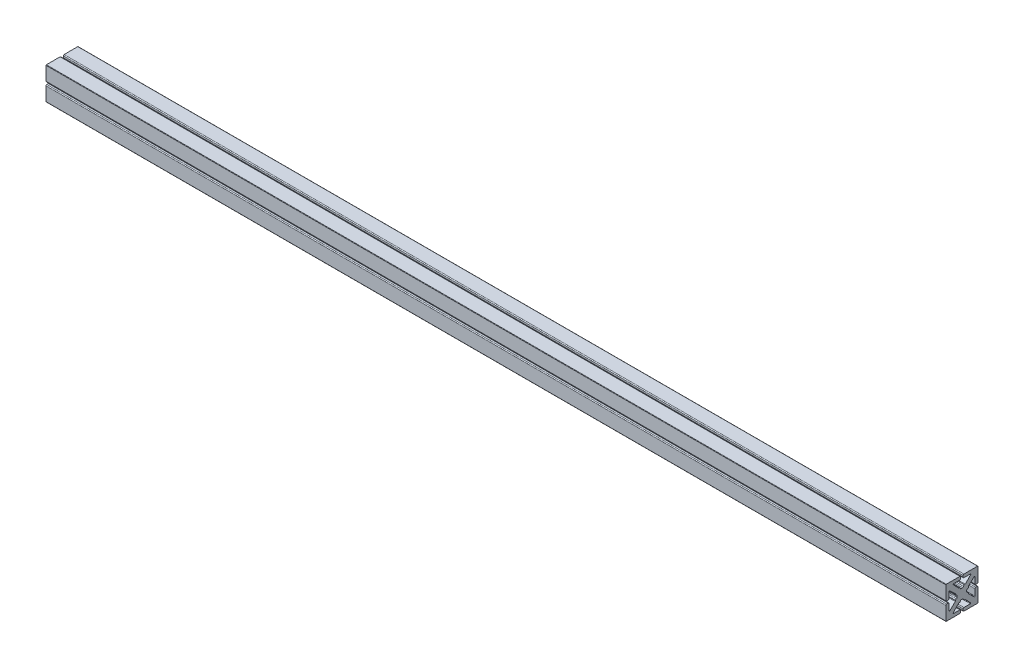
SolidWorks part; units mm, degrees
material "1060 Alloy"
ref_plane "Front Plane" through (0, 0, 0) normal (0, 0, 1) x (1, 0, 0)
ref_plane "Top Plane" through (0, 0, 0) normal (0, 1, 0) x (1, 0, 0)
ref_plane "Right Plane" through (0, 0, 0) normal (1, 0, 0) x (0, 0, -1)
sketch "Sketch1" plane through (0, 0, 0) normal (1, 0, 0) x (0, 0, -1)
  line L0 (0, 0) -> (0, 1.4986) construction
  line L1 (-0.2413, 1.4986) -> (0.2413, 1.4986)
  line L2 (5.0038, 0.635) -> (5.0038, 4.8768)
  line L3 (0.7493, 2.0066) -> (0.8825, 2.0066)
  line L4 (1.0655, 2.0845) -> (2.7141, 3.7982)
  line L5 (2.6226, 4.0132) -> (0.635, 4.0132)
  line L6 (0.381, 4.2672) -> (0.381, 4.7498)
  line L7 (0.635, 5.0038) -> (4.8768, 5.0038)
  line L8 (5.0038, 5.0038) -> (0, 0) construction
  line L9 (0, 0) -> (8.6271, 0) construction
  line L10 (0, 0) -> (0, 5.0038) construction
  line L11 (4.2672, 0.381) -> (4.7498, 0.381)
  line L12 (4.0132, 2.6226) -> (4.0132, 0.635)
  line L13 (2.0845, 1.0655) -> (3.7982, 2.7141)
  line L14 (2.0066, 0.7493) -> (2.0066, 0.8825)
  line L15 (1.4986, -0.2413) -> (1.4986, 0.2413)
  line L16 (0, 0) -> (1.4986, 0) construction
  line L17 (-0.2413, -1.4986) -> (0.2413, -1.4986)
  line L18 (0.7493, -2.0066) -> (0.8825, -2.0066)
  line L19 (1.0655, -2.0845) -> (2.7141, -3.7982)
  line L20 (2.6226, -4.0132) -> (0.635, -4.0132)
  line L21 (0.381, -4.2672) -> (0.381, -4.7498)
  line L22 (0.635, -5.0038) -> (4.8768, -5.0038)
  line L23 (5.0038, -0.635) -> (5.0038, -4.8768)
  line L24 (4.2672, -0.381) -> (4.7498, -0.381)
  line L25 (4.0132, -2.6226) -> (4.0132, -0.635)
  line L26 (2.0845, -1.0655) -> (3.7982, -2.7141)
  line L27 (2.0066, -0.7493) -> (2.0066, -0.8825)
  line L28 (-0.7493, 2.0066) -> (-0.8825, 2.0066)
  line L29 (-1.0655, 2.0845) -> (-2.7141, 3.7982)
  line L30 (-2.6226, 4.0132) -> (-0.635, 4.0132)
  line L31 (-0.381, 4.2672) -> (-0.381, 4.7498)
  line L32 (-0.635, 5.0038) -> (-4.8768, 5.0038)
  line L33 (-5.0038, 0.635) -> (-5.0038, 4.8768)
  line L34 (-4.2672, 0.381) -> (-4.7498, 0.381)
  line L35 (-4.0132, 2.6226) -> (-4.0132, 0.635)
  line L36 (-2.0845, 1.0655) -> (-3.7982, 2.7141)
  line L37 (-2.0066, 0.7493) -> (-2.0066, 0.8825)
  line L38 (-1.4986, -0.2413) -> (-1.4986, 0.2413)
  line L39 (-2.0066, -0.7493) -> (-2.0066, -0.8825)
  line L40 (-2.0845, -1.0655) -> (-3.7982, -2.7141)
  line L41 (-4.0132, -2.6226) -> (-4.0132, -0.635)
  line L42 (-4.2672, -0.381) -> (-4.7498, -0.381)
  line L43 (-5.0038, -0.635) -> (-5.0038, -4.8768)
  line L44 (-0.635, -5.0038) -> (-4.8768, -5.0038)
  line L45 (-0.381, -4.2672) -> (-0.381, -4.7498)
  line L46 (-2.6226, -4.0132) -> (-0.635, -4.0132)
  line L47 (-1.0655, -2.0845) -> (-2.7141, -3.7982)
  line L48 (-0.7493, -2.0066) -> (-0.8825, -2.0066)
  arc A0 (2.7141, 3.7982) -> (2.6226, 4.0132) centre (2.6226, 3.8862) ccw
  arc A1 (0.4953, 1.7526) -> (0.7493, 2.0066) centre (0.7493, 1.7526) cw
  arc A2 (0.8825, 2.0066) -> (1.0655, 2.0845) centre (0.8825, 2.2606) ccw
  arc A3 (0.635, 4.0132) -> (0.381, 4.2672) centre (0.635, 4.2672) cw
  arc A4 (0.381, 4.7498) -> (0.635, 5.0038) centre (0.635, 4.7498) cw
  arc A5 (0.2413, 1.4986) -> (0.4953, 1.7526) centre (0.2413, 1.7526) ccw
  arc A6 (4.7498, 0.381) -> (5.0038, 0.635) centre (4.7498, 0.635) ccw
  arc A7 (4.0132, 0.635) -> (4.2672, 0.381) centre (4.2672, 0.635) ccw
  arc A8 (3.7982, 2.7141) -> (4.0132, 2.6226) centre (3.8862, 2.6226) cw
  arc A9 (2.0066, 0.8825) -> (2.0845, 1.0655) centre (2.2606, 0.8825) cw
  arc A10 (1.7526, 0.4953) -> (2.0066, 0.7493) centre (1.7526, 0.7493) ccw
  arc A11 (1.4986, 0.2413) -> (1.7526, 0.4953) centre (1.7526, 0.2413) cw
  arc A12 (0.2413, -1.4986) -> (0.4953, -1.7526) centre (0.2413, -1.7526) cw
  arc A13 (0.4953, -1.7526) -> (0.7493, -2.0066) centre (0.7493, -1.7526) ccw
  arc A14 (0.8825, -2.0066) -> (1.0655, -2.0845) centre (0.8825, -2.2606) cw
  arc A15 (2.7141, -3.7982) -> (2.6226, -4.0132) centre (2.6226, -3.8862) cw
  arc A16 (0.635, -4.0132) -> (0.381, -4.2672) centre (0.635, -4.2672) ccw
  arc A17 (0.381, -4.7498) -> (0.635, -5.0038) centre (0.635, -4.7498) ccw
  arc A18 (4.7498, -0.381) -> (5.0038, -0.635) centre (4.7498, -0.635) cw
  arc A19 (4.0132, -0.635) -> (4.2672, -0.381) centre (4.2672, -0.635) cw
  arc A20 (3.7982, -2.7141) -> (4.0132, -2.6226) centre (3.8862, -2.6226) ccw
  arc A21 (2.0066, -0.8825) -> (2.0845, -1.0655) centre (2.2606, -0.8825) ccw
  arc A22 (1.7526, -0.4953) -> (2.0066, -0.7493) centre (1.7526, -0.7493) cw
  arc A23 (1.4986, -0.2413) -> (1.7526, -0.4953) centre (1.7526, -0.2413) ccw
  arc A24 (-0.2413, 1.4986) -> (-0.4953, 1.7526) centre (-0.2413, 1.7526) cw
  arc A25 (-0.4953, 1.7526) -> (-0.7493, 2.0066) centre (-0.7493, 1.7526) ccw
  arc A26 (-0.8825, 2.0066) -> (-1.0655, 2.0845) centre (-0.8825, 2.2606) cw
  arc A27 (-2.7141, 3.7982) -> (-2.6226, 4.0132) centre (-2.6226, 3.8862) cw
  arc A28 (-0.635, 4.0132) -> (-0.381, 4.2672) centre (-0.635, 4.2672) ccw
  arc A29 (-0.381, 4.7498) -> (-0.635, 5.0038) centre (-0.635, 4.7498) ccw
  arc A30 (-4.7498, 0.381) -> (-5.0038, 0.635) centre (-4.7498, 0.635) cw
  arc A31 (-4.0132, 0.635) -> (-4.2672, 0.381) centre (-4.2672, 0.635) cw
  arc A32 (-3.7982, 2.7141) -> (-4.0132, 2.6226) centre (-3.8862, 2.6226) ccw
  arc A33 (-2.0066, 0.8825) -> (-2.0845, 1.0655) centre (-2.2606, 0.8825) ccw
  arc A34 (-1.7526, 0.4953) -> (-2.0066, 0.7493) centre (-1.7526, 0.7493) cw
  arc A35 (-1.4986, 0.2413) -> (-1.7526, 0.4953) centre (-1.7526, 0.2413) ccw
  arc A36 (-1.4986, -0.2413) -> (-1.7526, -0.4953) centre (-1.7526, -0.2413) cw
  arc A37 (-1.7526, -0.4953) -> (-2.0066, -0.7493) centre (-1.7526, -0.7493) ccw
  arc A38 (-2.0066, -0.8825) -> (-2.0845, -1.0655) centre (-2.2606, -0.8825) cw
  arc A39 (-3.7982, -2.7141) -> (-4.0132, -2.6226) centre (-3.8862, -2.6226) cw
  arc A40 (-4.0132, -0.635) -> (-4.2672, -0.381) centre (-4.2672, -0.635) ccw
  arc A41 (-4.7498, -0.381) -> (-5.0038, -0.635) centre (-4.7498, -0.635) ccw
  arc A42 (-0.381, -4.7498) -> (-0.635, -5.0038) centre (-0.635, -4.7498) cw
  arc A43 (-0.635, -4.0132) -> (-0.381, -4.2672) centre (-0.635, -4.2672) cw
  arc A44 (-2.7141, -3.7982) -> (-2.6226, -4.0132) centre (-2.6226, -3.8862) ccw
  arc A45 (-0.8825, -2.0066) -> (-1.0655, -2.0845) centre (-0.8825, -2.2606) ccw
  arc A46 (-0.4953, -1.7526) -> (-0.7493, -2.0066) centre (-0.7493, -1.7526) cw
  arc A47 (-0.2413, -1.4986) -> (-0.4953, -1.7526) centre (-0.2413, -1.7526) ccw
  arc A48 (-4.8768, 5.0038) -> (-5.0038, 4.8768) centre (-4.8768, 4.8768) ccw
  arc A49 (-5.0038, -4.8768) -> (-4.8768, -5.0038) centre (-4.8768, -4.8768) ccw
  arc A50 (4.8768, -5.0038) -> (5.0038, -4.8768) centre (4.8768, -4.8768) ccw
  arc A51 (4.8768, 5.0038) -> (5.0038, 4.8768) centre (4.8768, 4.8768) cw
  point P14 (2.921, 4.0132)
  point P19 (0.9906, 2.0066)
  point P150 (0, -1.4986)
  point P152 (-5.0038, 5.0038)
  point P155 (-5.0038, -5.0038)
  point P158 (5.0038, -5.0038)
  dimension "D10" = 0.127
  dimension "D11" = 0.254
  dimension "D2" = 0.127
  dimension "D1" = 10.0076
  dimension "D3" = 2.9972
  dimension "D4" = 0.508
  dimension "D5" = 0.762
  dimension "D6" = 0.9906
  dimension "D7" = 2.54
  dimension "D8" = 1.9812
  dimension "D9" = 0.9906
extrude "Boss-Extrude1" add sketch "Sketch1" along normal blind 2.54 contours L33 A48 L32 A29 L31 A28 L30 A27 L29 A26 L28 A25 A24 L1 A5 A1 L3 A2 L4 A0 L5 A3 L6 A4 L7 A51 L2 A6 L11 A7 L12 A8 L13 A9 L14 A10 A11 L15 A23 A22 L27 A21 L26 A20 L25 A19 L24 A18 L23 A50 L22 A17 L21 A16 L20 A15 L19 A14 L18 A13 A12 L17 A47 A46 L48 A45 L47 A44 L46 A43 L45 A42 L44 A49 L43 A41 L42 A40 L41 A39 L40 A38 L39 A37 A36 L38 A35 A34 L37 A33 L36 A32 L35 A31 L34 A30
scale "Scale1" scale about centroid uniform scaling yes scale factor 8
sketch "Sketch2" plane through (0, 0, 0) normal (1, 0, 0) x (0, 0, -1)
  line L44 (-37.9984, 3.048) -> (-34.1376, 3.048)
  line L45 (-32.1056, 5.08) -> (-32.1056, 20.9808)
  line L46 (-30.3852, 21.7129) -> (-16.676, 8.5244)
  line L47 (-16.0528, 7.06) -> (-16.0528, 5.9944)
  line L48 (-11.9888, 1.9304) -> (-11.9888, -1.9304)
  line L49 (-16.0528, -5.9944) -> (-16.0528, -7.06)
  line L50 (-16.676, -8.5244) -> (-30.3852, -21.7129)
  line L51 (-32.1056, -20.9808) -> (-32.1056, -5.08)
  line L52 (-34.1376, -3.048) -> (-37.9984, -3.048)
  line L53 (-40.0304, -5.08) -> (-40.0304, -39.0144)
  line L54 (-39.0144, -40.0304) -> (-5.08, -40.0304)
  line L55 (-3.048, -37.9984) -> (-3.048, -34.1376)
  line L56 (-5.08, -32.1056) -> (-20.9808, -32.1056)
  line L57 (-21.7129, -30.3852) -> (-8.5244, -16.676)
  line L58 (-7.06, -16.0528) -> (-5.9944, -16.0528)
  line L59 (-1.9304, -11.9888) -> (1.9304, -11.9888)
  line L60 (5.9944, -16.0528) -> (7.06, -16.0528)
  line L61 (8.5244, -16.676) -> (21.7129, -30.3852)
  line L62 (20.9808, -32.1056) -> (5.08, -32.1056)
  line L63 (3.048, -34.1376) -> (3.048, -37.9984)
  line L64 (5.08, -40.0304) -> (39.0144, -40.0304)
  line L65 (40.0304, -39.0144) -> (40.0304, -5.08)
  line L66 (37.9984, -3.048) -> (34.1376, -3.048)
  line L67 (32.1056, -5.08) -> (32.1056, -20.9808)
  line L68 (30.3852, -21.7129) -> (16.676, -8.5244)
  line L69 (16.0528, -7.06) -> (16.0528, -5.9944)
  line L70 (11.9888, -1.9304) -> (11.9888, 1.9304)
  line L71 (16.0528, 5.9944) -> (16.0528, 7.06)
  line L72 (16.676, 8.5244) -> (30.3852, 21.7129)
  line L73 (32.1056, 20.9808) -> (32.1056, 5.08)
  line L74 (34.1376, 3.048) -> (37.9984, 3.048)
  line L75 (40.0304, 5.08) -> (40.0304, 39.0144)
  line L76 (39.0144, 40.0304) -> (5.08, 40.0304)
  line L77 (3.048, 37.9984) -> (3.048, 34.1376)
  line L78 (5.08, 32.1056) -> (20.9808, 32.1056)
  line L79 (21.7129, 30.3852) -> (8.5244, 16.676)
  line L80 (7.06, 16.0528) -> (5.9944, 16.0528)
  line L81 (1.9304, 11.9888) -> (-1.9304, 11.9888)
  line L82 (-5.9944, 16.0528) -> (-7.06, 16.0528)
  line L83 (-8.5244, 16.676) -> (-21.7129, 30.3852)
  line L84 (-20.9808, 32.1056) -> (-5.08, 32.1056)
  line L85 (-3.048, 34.1376) -> (-3.048, 37.9984)
  line L86 (-5.08, 40.0304) -> (-39.0144, 40.0304)
  line L87 (-40.0304, 39.0144) -> (-40.0304, 5.08)
  line L88 (-37.9984, 3.048) -> (-34.1376, 3.048)
  line L89 (-32.1056, 5.08) -> (-32.1056, 20.9808)
  line L90 (-30.3852, 21.7129) -> (-16.676, 8.5244)
  line L91 (-16.0528, 7.06) -> (-16.0528, 5.9944)
  line L92 (-11.9888, 1.9304) -> (-11.9888, -1.9304)
  line L93 (-16.0528, -5.9944) -> (-16.0528, -7.06)
  line L94 (-16.676, -8.5244) -> (-30.3852, -21.7129)
  line L95 (-32.1056, -20.9808) -> (-32.1056, -5.08)
  line L96 (-34.1376, -3.048) -> (-37.9984, -3.048)
  line L97 (-40.0304, -5.08) -> (-40.0304, -39.0144)
  line L98 (-39.0144, -40.0304) -> (-5.08, -40.0304)
  line L99 (-3.048, -37.9984) -> (-3.048, -34.1376)
  line L100 (-5.08, -32.1056) -> (-20.9808, -32.1056)
  line L101 (-21.7129, -30.3852) -> (-8.5244, -16.676)
  line L102 (-7.06, -16.0528) -> (-5.9944, -16.0528)
  line L103 (-1.9304, -11.9888) -> (1.9304, -11.9888)
  line L104 (5.9944, -16.0528) -> (7.06, -16.0528)
  line L105 (8.5244, -16.676) -> (21.7129, -30.3852)
  line L106 (20.9808, -32.1056) -> (5.08, -32.1056)
  line L107 (3.048, -34.1376) -> (3.048, -37.9984)
  line L108 (5.08, -40.0304) -> (39.0144, -40.0304)
  line L109 (40.0304, -39.0144) -> (40.0304, -5.08)
  line L110 (37.9984, -3.048) -> (34.1376, -3.048)
  line L111 (32.1056, -5.08) -> (32.1056, -20.9808)
  line L112 (30.3852, -21.7129) -> (16.676, -8.5244)
  line L113 (16.0528, -7.06) -> (16.0528, -5.9944)
  line L114 (11.9888, -1.9304) -> (11.9888, 1.9304)
  line L115 (16.0528, 5.9944) -> (16.0528, 7.06)
  line L116 (16.676, 8.5244) -> (30.3852, 21.7129)
  line L117 (32.1056, 20.9808) -> (32.1056, 5.08)
  line L118 (34.1376, 3.048) -> (37.9984, 3.048)
  line L119 (40.0304, 5.08) -> (40.0304, 39.0144)
  line L120 (39.0144, 40.0304) -> (5.08, 40.0304)
  line L121 (3.048, 37.9984) -> (3.048, 34.1376)
  line L122 (5.08, 32.1056) -> (20.9808, 32.1056)
  line L123 (21.7129, 30.3852) -> (8.5244, 16.676)
  line L124 (7.06, 16.0528) -> (5.9944, 16.0528)
  line L125 (1.9304, 11.9888) -> (-1.9304, 11.9888)
  line L126 (-5.9944, 16.0528) -> (-7.06, 16.0528)
  line L127 (-8.5244, 16.676) -> (-21.7129, 30.3852)
  line L128 (-20.9808, 32.1056) -> (-5.08, 32.1056)
  line L129 (-3.048, 34.1376) -> (-3.048, 37.9984)
  line L130 (-5.08, 40.0304) -> (-39.0144, 40.0304)
  line L131 (-40.0304, 39.0144) -> (-40.0304, 5.08)
  arc A52 (-40.0304, 5.08) -> (-37.9984, 3.048) centre (-37.9984, 5.08) ccw
  arc A53 (-34.1376, 3.048) -> (-32.1056, 5.08) centre (-34.1376, 5.08) ccw
  arc A54 (-30.3852, 21.7129) -> (-32.1056, 20.9808) centre (-31.0896, 20.9808) ccw
  arc A55 (-16.0528, 7.06) -> (-16.676, 8.5244) centre (-18.0848, 7.06) ccw
  arc A56 (-16.0528, 5.9944) -> (-14.0208, 3.9624) centre (-14.0208, 5.9944) ccw
  arc A57 (-11.9888, 1.9304) -> (-14.0208, 3.9624) centre (-14.0208, 1.9304) ccw
  arc A58 (-14.0208, -3.9624) -> (-11.9888, -1.9304) centre (-14.0208, -1.9304) ccw
  arc A59 (-14.0208, -3.9624) -> (-16.0528, -5.9944) centre (-14.0208, -5.9944) ccw
  arc A60 (-16.676, -8.5244) -> (-16.0528, -7.06) centre (-18.0848, -7.06) ccw
  arc A61 (-32.1056, -20.9808) -> (-30.3852, -21.7129) centre (-31.0896, -20.9808) ccw
  arc A62 (-32.1056, -5.08) -> (-34.1376, -3.048) centre (-34.1376, -5.08) ccw
  arc A63 (-37.9984, -3.048) -> (-40.0304, -5.08) centre (-37.9984, -5.08) ccw
  arc A64 (-40.0304, -39.0144) -> (-39.0144, -40.0304) centre (-39.0144, -39.0144) ccw
  arc A65 (-5.08, -40.0304) -> (-3.048, -37.9984) centre (-5.08, -37.9984) ccw
  arc A66 (-3.048, -34.1376) -> (-5.08, -32.1056) centre (-5.08, -34.1376) ccw
  arc A67 (-21.7129, -30.3852) -> (-20.9808, -32.1056) centre (-20.9808, -31.0896) ccw
  arc A68 (-7.06, -16.0528) -> (-8.5244, -16.676) centre (-7.06, -18.0848) ccw
  arc A69 (-5.9944, -16.0528) -> (-3.9624, -14.0208) centre (-5.9944, -14.0208) ccw
  arc A70 (-1.9304, -11.9888) -> (-3.9624, -14.0208) centre (-1.9304, -14.0208) ccw
  arc A71 (3.9624, -14.0208) -> (1.9304, -11.9888) centre (1.9304, -14.0208) ccw
  arc A72 (3.9624, -14.0208) -> (5.9944, -16.0528) centre (5.9944, -14.0208) ccw
  arc A73 (8.5244, -16.676) -> (7.06, -16.0528) centre (7.06, -18.0848) ccw
  arc A74 (20.9808, -32.1056) -> (21.7129, -30.3852) centre (20.9808, -31.0896) ccw
  arc A75 (5.08, -32.1056) -> (3.048, -34.1376) centre (5.08, -34.1376) ccw
  arc A76 (3.048, -37.9984) -> (5.08, -40.0304) centre (5.08, -37.9984) ccw
  arc A77 (39.0144, -40.0304) -> (40.0304, -39.0144) centre (39.0144, -39.0144) ccw
  arc A78 (40.0304, -5.08) -> (37.9984, -3.048) centre (37.9984, -5.08) ccw
  arc A79 (34.1376, -3.048) -> (32.1056, -5.08) centre (34.1376, -5.08) ccw
  arc A80 (30.3852, -21.7129) -> (32.1056, -20.9808) centre (31.0896, -20.9808) ccw
  arc A81 (16.0528, -7.06) -> (16.676, -8.5244) centre (18.0848, -7.06) ccw
  arc A82 (16.0528, -5.9944) -> (14.0208, -3.9624) centre (14.0208, -5.9944) ccw
  arc A83 (11.9888, -1.9304) -> (14.0208, -3.9624) centre (14.0208, -1.9304) ccw
  arc A84 (14.0208, 3.9624) -> (11.9888, 1.9304) centre (14.0208, 1.9304) ccw
  arc A85 (14.0208, 3.9624) -> (16.0528, 5.9944) centre (14.0208, 5.9944) ccw
  arc A86 (16.676, 8.5244) -> (16.0528, 7.06) centre (18.0848, 7.06) ccw
  arc A87 (32.1056, 20.9808) -> (30.3852, 21.7129) centre (31.0896, 20.9808) ccw
  arc A88 (32.1056, 5.08) -> (34.1376, 3.048) centre (34.1376, 5.08) ccw
  arc A89 (37.9984, 3.048) -> (40.0304, 5.08) centre (37.9984, 5.08) ccw
  arc A90 (40.0304, 39.0144) -> (39.0144, 40.0304) centre (39.0144, 39.0144) ccw
  arc A91 (5.08, 40.0304) -> (3.048, 37.9984) centre (5.08, 37.9984) ccw
  arc A92 (3.048, 34.1376) -> (5.08, 32.1056) centre (5.08, 34.1376) ccw
  arc A93 (21.7129, 30.3852) -> (20.9808, 32.1056) centre (20.9808, 31.0896) ccw
  arc A94 (7.06, 16.0528) -> (8.5244, 16.676) centre (7.06, 18.0848) ccw
  arc A95 (5.9944, 16.0528) -> (3.9624, 14.0208) centre (5.9944, 14.0208) ccw
  arc A96 (1.9304, 11.9888) -> (3.9624, 14.0208) centre (1.9304, 14.0208) ccw
  arc A97 (-3.9624, 14.0208) -> (-1.9304, 11.9888) centre (-1.9304, 14.0208) ccw
  arc A98 (-3.9624, 14.0208) -> (-5.9944, 16.0528) centre (-5.9944, 14.0208) ccw
  arc A99 (-8.5244, 16.676) -> (-7.06, 16.0528) centre (-7.06, 18.0848) ccw
  arc A100 (-20.9808, 32.1056) -> (-21.7129, 30.3852) centre (-20.9808, 31.0896) ccw
  arc A101 (-5.08, 32.1056) -> (-3.048, 34.1376) centre (-5.08, 34.1376) ccw
  arc A102 (-3.048, 37.9984) -> (-5.08, 40.0304) centre (-5.08, 37.9984) ccw
  arc A103 (-39.0144, 40.0304) -> (-40.0304, 39.0144) centre (-39.0144, 39.0144) ccw
  arc A104 (-40.0304, 5.08) -> (-37.9984, 3.048) centre (-37.9984, 5.08) ccw
  arc A105 (-34.1376, 3.048) -> (-32.1056, 5.08) centre (-34.1376, 5.08) ccw
  arc A106 (-30.3852, 21.7129) -> (-32.1056, 20.9808) centre (-31.0896, 20.9808) ccw
  arc A107 (-16.0528, 7.06) -> (-16.676, 8.5244) centre (-18.0848, 7.06) ccw
  arc A108 (-16.0528, 5.9944) -> (-14.0208, 3.9624) centre (-14.0208, 5.9944) ccw
  arc A109 (-11.9888, 1.9304) -> (-14.0208, 3.9624) centre (-14.0208, 1.9304) ccw
  arc A110 (-14.0208, -3.9624) -> (-11.9888, -1.9304) centre (-14.0208, -1.9304) ccw
  arc A111 (-14.0208, -3.9624) -> (-16.0528, -5.9944) centre (-14.0208, -5.9944) ccw
  arc A112 (-16.676, -8.5244) -> (-16.0528, -7.06) centre (-18.0848, -7.06) ccw
  arc A113 (-32.1056, -20.9808) -> (-30.3852, -21.7129) centre (-31.0896, -20.9808) ccw
  arc A114 (-32.1056, -5.08) -> (-34.1376, -3.048) centre (-34.1376, -5.08) ccw
  arc A115 (-37.9984, -3.048) -> (-40.0304, -5.08) centre (-37.9984, -5.08) ccw
  arc A116 (-40.0304, -39.0144) -> (-39.0144, -40.0304) centre (-39.0144, -39.0144) ccw
  arc A117 (-5.08, -40.0304) -> (-3.048, -37.9984) centre (-5.08, -37.9984) ccw
  arc A118 (-3.048, -34.1376) -> (-5.08, -32.1056) centre (-5.08, -34.1376) ccw
  arc A119 (-21.7129, -30.3852) -> (-20.9808, -32.1056) centre (-20.9808, -31.0896) ccw
  arc A120 (-7.06, -16.0528) -> (-8.5244, -16.676) centre (-7.06, -18.0848) ccw
  arc A121 (-5.9944, -16.0528) -> (-3.9624, -14.0208) centre (-5.9944, -14.0208) ccw
  arc A122 (-1.9304, -11.9888) -> (-3.9624, -14.0208) centre (-1.9304, -14.0208) ccw
  arc A123 (3.9624, -14.0208) -> (1.9304, -11.9888) centre (1.9304, -14.0208) ccw
  arc A124 (3.9624, -14.0208) -> (5.9944, -16.0528) centre (5.9944, -14.0208) ccw
  arc A125 (8.5244, -16.676) -> (7.06, -16.0528) centre (7.06, -18.0848) ccw
  arc A126 (20.9808, -32.1056) -> (21.7129, -30.3852) centre (20.9808, -31.0896) ccw
  arc A127 (5.08, -32.1056) -> (3.048, -34.1376) centre (5.08, -34.1376) ccw
  arc A128 (3.048, -37.9984) -> (5.08, -40.0304) centre (5.08, -37.9984) ccw
  arc A129 (39.0144, -40.0304) -> (40.0304, -39.0144) centre (39.0144, -39.0144) ccw
  arc A130 (40.0304, -5.08) -> (37.9984, -3.048) centre (37.9984, -5.08) ccw
  arc A131 (34.1376, -3.048) -> (32.1056, -5.08) centre (34.1376, -5.08) ccw
  arc A132 (30.3852, -21.7129) -> (32.1056, -20.9808) centre (31.0896, -20.9808) ccw
  arc A133 (16.0528, -7.06) -> (16.676, -8.5244) centre (18.0848, -7.06) ccw
  arc A134 (16.0528, -5.9944) -> (14.0208, -3.9624) centre (14.0208, -5.9944) ccw
  arc A135 (11.9888, -1.9304) -> (14.0208, -3.9624) centre (14.0208, -1.9304) ccw
  arc A136 (14.0208, 3.9624) -> (11.9888, 1.9304) centre (14.0208, 1.9304) ccw
  arc A137 (14.0208, 3.9624) -> (16.0528, 5.9944) centre (14.0208, 5.9944) ccw
  arc A138 (16.676, 8.5244) -> (16.0528, 7.06) centre (18.0848, 7.06) ccw
  arc A139 (32.1056, 20.9808) -> (30.3852, 21.7129) centre (31.0896, 20.9808) ccw
  arc A140 (32.1056, 5.08) -> (34.1376, 3.048) centre (34.1376, 5.08) ccw
  arc A141 (37.9984, 3.048) -> (40.0304, 5.08) centre (37.9984, 5.08) ccw
  arc A142 (40.0304, 39.0144) -> (39.0144, 40.0304) centre (39.0144, 39.0144) ccw
  arc A143 (5.08, 40.0304) -> (3.048, 37.9984) centre (5.08, 37.9984) ccw
  arc A144 (3.048, 34.1376) -> (5.08, 32.1056) centre (5.08, 34.1376) ccw
  arc A145 (21.7129, 30.3852) -> (20.9808, 32.1056) centre (20.9808, 31.0896) ccw
  arc A146 (7.06, 16.0528) -> (8.5244, 16.676) centre (7.06, 18.0848) ccw
  arc A147 (5.9944, 16.0528) -> (3.9624, 14.0208) centre (5.9944, 14.0208) ccw
  arc A148 (1.9304, 11.9888) -> (3.9624, 14.0208) centre (1.9304, 14.0208) ccw
  arc A149 (-3.9624, 14.0208) -> (-1.9304, 11.9888) centre (-1.9304, 14.0208) ccw
  arc A150 (-3.9624, 14.0208) -> (-5.9944, 16.0528) centre (-5.9944, 14.0208) ccw
  arc A151 (-8.5244, 16.676) -> (-7.06, 16.0528) centre (-7.06, 18.0848) ccw
  arc A152 (-20.9808, 32.1056) -> (-21.7129, 30.3852) centre (-20.9808, 31.0896) ccw
  arc A153 (-5.08, 32.1056) -> (-3.048, 34.1376) centre (-5.08, 34.1376) ccw
  arc A154 (-3.048, 37.9984) -> (-5.08, 40.0304) centre (-5.08, 37.9984) ccw
  arc A155 (-39.0144, 40.0304) -> (-40.0304, 39.0144) centre (-39.0144, 39.0144) ccw
  dimension "D1" = 0
extrude "Boss-Extrude2" add sketch "Sketch2" along normal mid plane 2240
ref_point "Point1"
ref_point "Point2"
